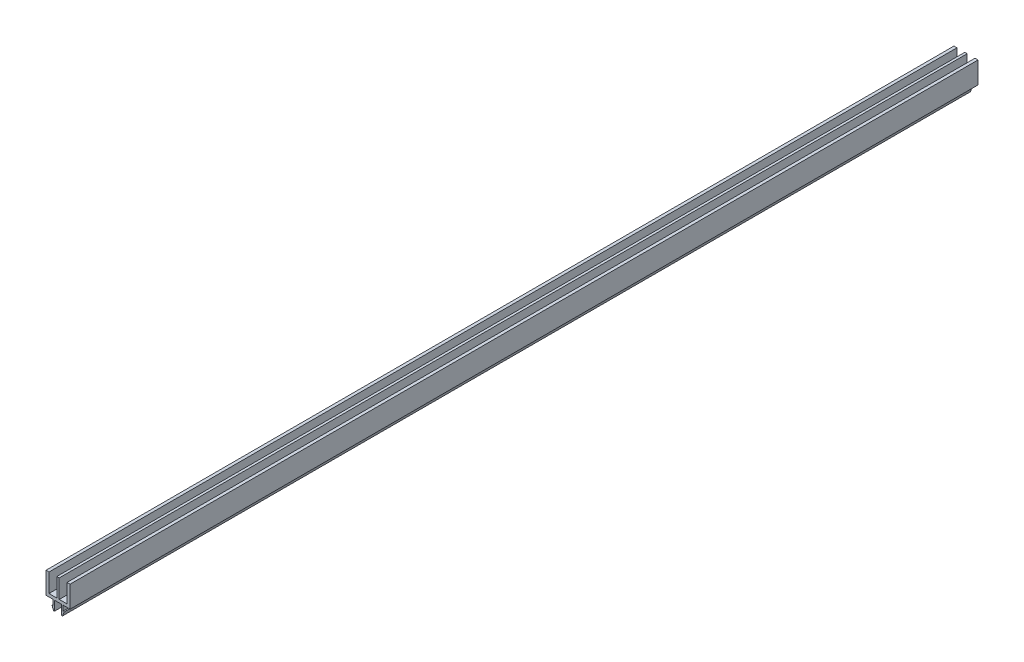
SolidWorks part; units mm, degrees
ref_plane "Plan de face" through (0, 0, 0) normal (0, 0, 1) x (1, 0, 0)
ref_plane "Plan de dessus" through (0, 0, 0) normal (0, 1, 0) x (1, 0, 0)
ref_plane "Plan de droite" through (0, 0, 0) normal (1, 0, 0) x (0, 0, -1)
ref_plane "Plan1" through (0, 0, 50) normal (0, 0, 1) x (1, 0, 0)
sketch "Esquisse1" plane through (0, 0, 50) normal (0, 0, 1) x (1, 0, 0)
  line L0 (-1, 2.5) -> (-7.5, 2.5)
  line L1 (-7.5, 2.5) -> (-7.5, 18)
  line L2 (-7.5, 18) -> (-10, 18)
  line L3 (-10, 18) -> (-10, 0)
  line L4 (-10, 0) -> (-4, 0)
  line L5 (-4, 0) -> (-4, -4.5)
  line L6 (-4, -4.5) -> (-5, -4.5)
  line L7 (-5, -4.5) -> (-3.75, -8)
  line L8 (-3.75, -8) -> (-3, -8)
  line L9 (-3, -8) -> (-3, 0)
  line L10 (-3, 0) -> (3, 0)
  line L11 (3, 0) -> (3, -8)
  line L12 (3, -8) -> (3.75, -8)
  line L13 (3.75, -8) -> (5, -4.5)
  line L14 (5, -4.5) -> (4, -4.5)
  line L15 (4, -4.5) -> (4, 0)
  line L16 (4, 0) -> (10, 0)
  line L17 (10, 0) -> (10, 18)
  line L18 (10, 18) -> (7.5, 18)
  line L19 (7.5, 18) -> (7.5, 2.5)
  line L20 (7.5, 2.5) -> (1, 2.5)
  line L21 (1, 2.5) -> (1, 18)
  line L22 (1, 18) -> (-1, 18)
  line L23 (-1, 18) -> (-1, 2.5)
extrude "Boss.-Extru.1" add sketch "Esquisse1" against normal blind 754
